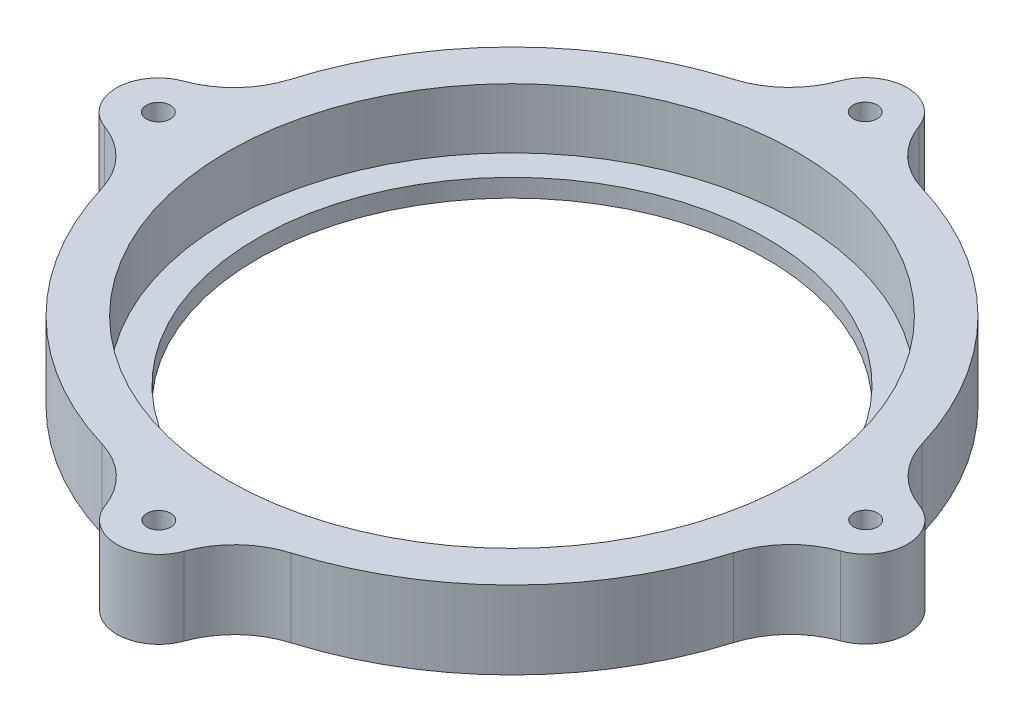
SolidWorks part; units mm, degrees
ref_plane "Front Plane" through (0, 0, 0) normal (0, 0, 1) x (1, 0, 0)
ref_plane "Top Plane" through (0, 0, 0) normal (0, 1, 0) x (1, 0, 0)
ref_plane "Right Plane" through (0, 0, 0) normal (1, 0, 0) x (0, 0, -1)
other "Graphic1"
other "Graphic (Closed) -1"
sketch "Sketch1" plane through (0, 0, 0) normal (0, 1, 0) x (1, 0, 0)
  line L0 (58.4365, 1.919) -> (59.5406, -1.8413) construction
  line L1 (59, -2) -> (60.0813, -1.6825) construction
  arc A0 (52.6872, 15.7815) -> (52.708, -15.7121) centre (0, 0) ccw
  circle A1 centre (58.9886, 0.0389) radius 2
  arc A2 (61.3672, -6.5446) -> (61.3586, 6.6255) centre (58.9886, 0.0389) ccw
  arc A3 (61.3672, -6.5446) -> (52.708, -15.7121) centre (66.1245, -19.7115) ccw
  arc A4 (61.3586, 6.6255) -> (52.6872, 15.7815) centre (66.0985, 19.7986) cw
  arc A5 (-6.5446, -61.3672) -> (-15.7121, -52.708) centre (-19.7115, -66.1245) ccw
  arc A6 (-6.5446, -61.3672) -> (6.6255, -61.3586) centre (0.0389, -58.9886) ccw
  circle A7 centre (0.0389, -58.9886) radius 2
  arc A8 (6.6255, -61.3586) -> (15.7815, -52.6872) centre (19.7986, -66.0985) cw
  arc A9 (-61.3672, 6.5446) -> (-52.708, 15.7121) centre (-66.1245, 19.7115) ccw
  arc A10 (-61.3672, 6.5446) -> (-61.3586, -6.6255) centre (-58.9886, -0.0389) ccw
  circle A11 centre (-58.9886, -0.0389) radius 2
  arc A12 (-61.3586, -6.6255) -> (-52.6872, -15.7815) centre (-66.0985, -19.7986) cw
  arc A13 (6.5446, 61.3672) -> (15.7121, 52.708) centre (19.7115, 66.1245) ccw
  arc A14 (6.5446, 61.3672) -> (-6.6255, 61.3586) centre (-0.0389, 58.9886) ccw
  circle A15 centre (-0.0389, 58.9886) radius 2
  arc A16 (-6.6255, 61.3586) -> (-15.7815, 52.6872) centre (-19.7986, 66.0985) cw
  point P10 (59.5406, -1.8413)
  point P45 (0, 0)
  dimension "D1" = 14
extrude "Boss-Extrude1" add sketch "Sketch1" against normal blind 13 contours A2 A4 A0 A3 A1 | A6 A8 A0 A5 A7 | A10 A12 A0 A9 A11 | A14 A16 A0 A13 A15
sketch "Sketch2" plane through (0, 0, 0) normal (0, 1, 0) x (1, 0, 0)
  circle A0 centre (0, 0) radius 47.5
extrude "Cut-Extrude1" cut sketch "Sketch2" against normal blind 10
sketch "Sketch3" plane through (0, -10, 0) normal (0, 1, 0) x (1, 0, 0)
  circle A0 centre (0, 0) radius 42.5
extrude "Cut-Extrude2" cut sketch "Sketch3" against normal blind 10
